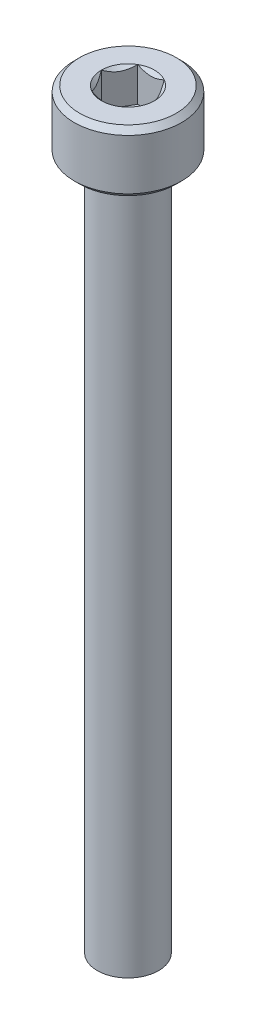
SolidWorks part; units mm, degrees
ref_plane "Front" through (0, 0, 0) normal (0, 0, 1) x (1, 0, 0)
ref_plane "Top" through (0, 0, 0) normal (0, 1, 0) x (1, 0, 0)
ref_plane "Right" through (0, 0, 0) normal (1, 0, 0) x (0, 0, -1)
sketch "Sketch1" plane through (0, 0, 0) normal (0, 1, 0) x (1, 0, 0)
  circle A0 centre (0, 0) radius 3.5
  dimension "D1" = 7
extrude "Boss-Extrude1" add sketch "Sketch1" along normal blind 4
sketch "Sketch2" plane through (0, 4, 0) normal (0, 1, 0) x (1, 0, 0)
  line L1 (0.866, 1.5) -> (-0.866, 1.5)
  line L2 (-0.866, 1.5) -> (-1.7321, 0)
  line L3 (-1.7321, 0) -> (-0.866, -1.5)
  line L4 (-0.866, -1.5) -> (0.866, -1.5)
  line L5 (0.866, -1.5) -> (1.7321, 0)
  line L6 (1.7321, 0) -> (0.866, 1.5)
  circle A0 centre (0, 0) radius 1.5 construction
  point P10 (0, 1.5)
  dimension "D1" = 3
extrude "Cut-Extrude1" cut sketch "Sketch2" against normal blind 2.25
sketch "Sketch3" plane through (0, 4, 0) normal (0, 1, 0) x (1, 0, 0)
  circle A0 centre (0, 0) radius 1.7321
extrude "Cut-Extrude2" cut sketch "Sketch3" against normal through all draft 45
chamfer "Chamfer1" distance 0.35 angle 45 2 edges at (0, 0, 3.5) (0, 4, 3.5)
sketch "草图1" plane through (0, 0, 0) normal (0, -1, 0) x (-1, 0, 0)
  circle A0 centre (0, 0) radius 2
  dimension "D1" = 4
extrude "凸台-拉伸1" add sketch "草图1" along normal blind 45
